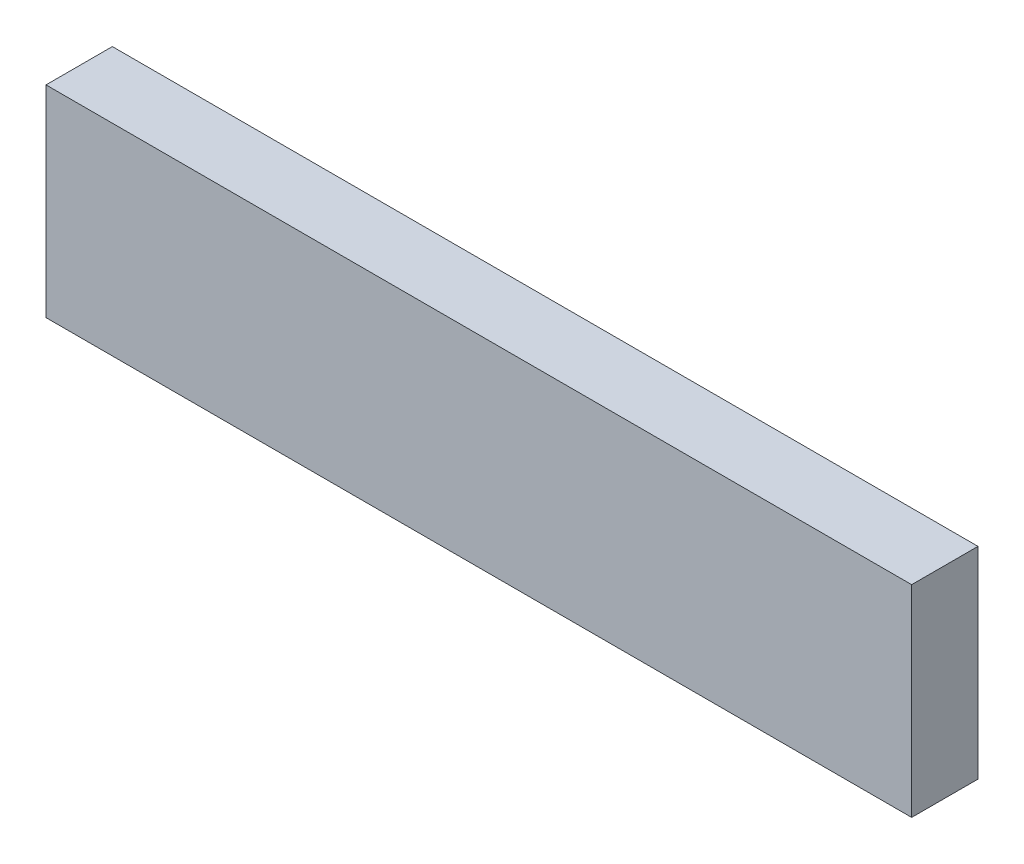
SolidWorks part; units mm, degrees
ref_plane "Спереди" through (0, 0, 0) normal (0, 0, 1) x (1, 0, 0)
ref_plane "Сверху" through (0, 0, 0) normal (0, 1, 0) x (1, 0, 0)
ref_plane "Справа" through (0, 0, 0) normal (1, 0, 0) x (0, 0, -1)
sketch "Эскиз1" plane through (0, 0, 0) normal (0, 0, 1) x (1, 0, 0)
  line L1 (-65.2365, -15.1923) -> (65.2365, -15.1923)
  line L2 (-65.2365, -15.1923) -> (-65.2365, 15.1923)
  line L3 (-65.2365, 15.1923) -> (65.2365, 15.1923)
  line L4 (65.2365, -15.1923) -> (65.2365, 15.1923)
  line L5 (-65.2365, -15.1923) -> (65.2365, 15.1923) construction
  line L6 (-65.2365, 15.1923) -> (65.2365, -15.1923) construction
  point P0 (0, 0)
  point P7 (-65.2942, -3.4887)
extrude "Бобышка-Вытянуть1" add sketch "Эскиз1" along normal blind 10
sketch "шлиф" plane through (0, 0, 10) normal (0, 0, 1) x (1, 0, 0)
  line L1 (-61.9854, 2.0495) -> (61.9854, 2.0495)
  line L2 (-61.9854, 2.0495) -> (-61.9854, -2.0495)
  line L3 (-61.9854, -2.0495) -> (61.9854, -2.0495)
  line L4 (61.9854, 2.0495) -> (61.9854, -2.0495)
  line L5 (-61.9854, 2.0495) -> (61.9854, -2.0495) construction
  line L6 (-61.9854, -2.0495) -> (61.9854, 2.0495) construction
  point P0 (0, 0)
